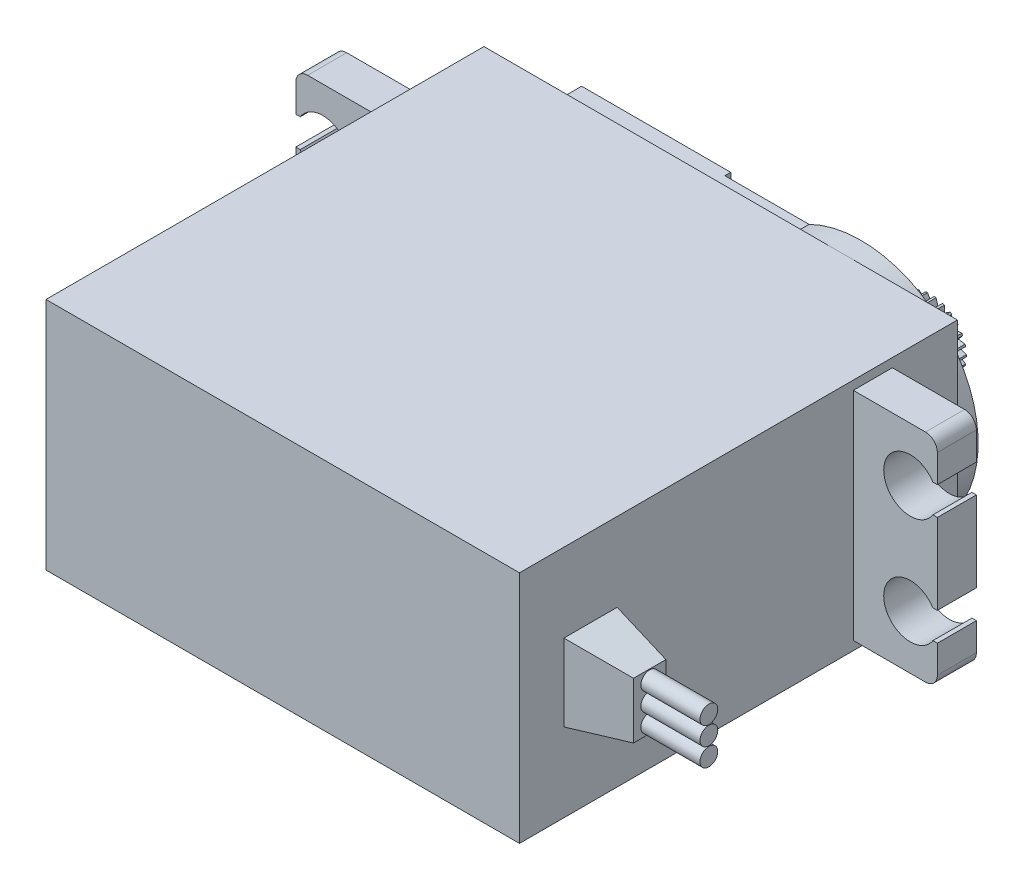
SolidWorks part; units mm, degrees
ref_plane "Front Plane" through (0, 0, 0) normal (0, 0, 1) x (1, 0, 0)
ref_plane "Top Plane" through (0, 0, 0) normal (0, 1, 0) x (1, 0, 0)
ref_plane "Right Plane" through (0, 0, 0) normal (1, 0, 0) x (0, 0, -1)
sketch "Sketch1" plane through (0, 0, 0) normal (0, 1, 0) x (1, 0, 0)
  line L1 (-20, -18.5) -> (20, -18.5)
  line L2 (-20, -18.5) -> (-20, 18.5)
  line L3 (-20, 18.5) -> (20, 18.5)
  line L4 (20, -18.5) -> (20, 18.5)
  line L5 (-20, -18.5) -> (20, 18.5) construction
  line L6 (-20, 18.5) -> (20, -18.5) construction
  point P0 (0, 0)
  dimension "D1" = 40
  dimension "D2" = 37
extrude "Boss-Extrude1" add sketch "Sketch1" along normal mid plane 19.8
sketch "Sketch2" plane through (0, 0, -18.5) normal (0, 0, -1) x (-1, 0, 0)
  line L0 (20.35, 0) -> (-20.35, 0) construction
  line L1 (-20, 9.9) -> (20, 9.9) construction
  line L2 (-20, 9.9) -> (-20, -9.9) construction
  line L3 (20, 9.9) -> (20, -9.9) construction
  line L4 (-5.7132, -8.875) -> (14, -8.875)
  line L6 (-5.7132, 8.875) -> (14, 8.875)
  line L7 (14, -8.875) -> (14, -4.625)
  line L8 (-5.7132, -8.875) -> (14, 8.875) construction
  line L9 (-5.7132, 8.875) -> (14, -8.875) construction
  line L10 (14, 4.625) -> (14, 8.875)
  circle A0 centre (-10.1, 0) radius 9.9
  arc A1 (14, 4.625) -> (14, -4.625) centre (10.3715, 0) cw
  point P8 (4.1434, 0)
  point P19 (16.25, 0)
  dimension "D4" = 3.75
  dimension "D1" = 17.75
  dimension "D2" = 6
  dimension "D3" = 9.25
extrude "Boss-Extrude2" add sketch "Sketch2" along normal blind 1.75 contours A0 | A0 L4 L7 L6
sketch "Sketch3" plane through (0, 0, -20.25) normal (0, 0, -1) x (-1, 0, 0)
  circle A0 centre (-10.1, 0) radius 6.55
  dimension "D1" = 13.1
extrude "Boss-Extrude3" add sketch "Sketch3" along normal blind 1.25
sketch "Sketch4" plane through (0, 0, -21.5) normal (0, 0, -1) x (-1, 0, 0)
  circle A0 centre (-10.1, 0) radius 5.375
  dimension "D1" = 10.75
extrude "Boss-Extrude4" add sketch "Sketch4" along normal blind 0.65
ref_plane "Plane1" through (10.1, 0, 0) normal (1, 0, 0) x (0, 0, -1)
sketch "Sketch5" plane through (-20, 0, 0) normal (-1, 0, 0) x (0, 0, 1)
  line L0 (20.35, 0) -> (-20.35, 0) construction
  line L1 (-13, -9.15) -> (-9.7, -9.15)
  line L2 (-13, -9.15) -> (-13, 9.15)
  line L3 (-13, 9.15) -> (-9.7, 9.15)
  line L4 (-9.7, -9.15) -> (-9.7, 9.15)
  line L5 (-13, -9.15) -> (-9.7, 9.15) construction
  line L6 (-13, 9.15) -> (-9.7, -9.15) construction
  line L7 (-18.5, 9.9) -> (-18.5, -9.9) construction
  point P0 (-11.35, 0)
  dimension "D1" = 18.3
  dimension "D2" = 3.3
  dimension "D3" = 5.5
extrude "Boss-Extrude5" add sketch "Sketch5" along normal blind 7.1
sketch "Sketch6" plane through (0, 0, -13) normal (0, 0, -1) x (-1, 0, 0)
  line L1 (20, 9.15) -> (20, -9.15) construction
  line L2 (27.1, 9.15) -> (20, 9.15) construction
  line L4 (27.1, 3.4) -> (27.1, 5.8)
  line L5 (27.1, 9.15) -> (27.1, -9.15) construction
  line L6 (27.1, 5.8) -> (26.7233, 5.8)
  line L7 (27.1, 3.4) -> (26.7233, 3.4)
  circle A0 centre (24.82, 4.6) radius 2.25
  point P11 (27.1, 4.6)
  line M5 (27.1, -9.15) -> (27.1, 9.15)
  dimension "D1" = 4.5
  dimension "D2" = 2.4
  dimension "D3" = 4.82
  dimension "D4" = 4.55
extrude "Cut-Extrude1" cut sketch "Sketch6" against normal up to surface (3.3 mm away) contours A0 L7 L6 M5 | A0 up to face at (-23.55, 0, -9.7)
mirror "Mirror1" about plane through (0, 0, 0) normal (0, 1, 0) of "Cut-Extrude1"
fillet "Fillet1" radius 1 2 edges at (-27.1, 9.15, -11.35) (-27.1, -9.15, -11.35)
mirror "Mirror4" about plane through (0, 0, 0) normal (1, 0, 0) of "Fillet1", "Boss-Extrude5", "Cut-Extrude1", "Mirror1"
sketch "Sketch8" plane through (0, 0, -20.25) normal (0, 0, -1) x (-1, 0, 0)
  line L0 (14, 4.625) -> (14, 8.875) construction
  line L1 (14, 8.875) -> (1.4, 8.875)
  line L2 (14, 8.875) -> (14, -8.875)
  line L3 (14, -8.875) -> (1.4, -8.875)
  line L4 (1.4, 8.875) -> (1.4, -8.875)
  line L5 (14, 4.625) -> (14, 8.875) construction
  line L6 (-5.7132, -8.875) -> (14, -8.875) construction
  line L7 (-5.7132, 8.875) -> (14, 8.875) construction
  arc A0 (1.4, 1.875) -> (1.4, -1.875) centre (1.4, 0) ccw
  line M3 (14, 8.875) -> (-5.7132, 8.875)
  line M5 (-5.7132, -8.875) -> (14, -8.875)
  line M6 (14, -8.875) -> (14, -4.625)
  line M8 (14, 4.625) -> (14, 8.875)
  dimension "D2" = 1.875
  dimension "D1" = 12.6
extrude "Boss-Extrude6" add sketch "Sketch8" along normal blind 0.5 contours L4 A0 | L4 L2 M3 M5 M6 M8
sketch "Sketch9" plane through (20, 0, 0) normal (1, 0, 0) x (0, 0, -1)
  line L0 (22.3575, 0) -> (-22.3575, 0) construction
  line L1 (-14.75, -3.25) -> (-10.25, -3.25)
  line L2 (-14.75, -3.25) -> (-14.75, 3.25)
  line L3 (-14.75, 3.25) -> (-10.25, 3.25)
  line L4 (-10.25, -3.25) -> (-10.25, 3.25)
  line L5 (-14.75, -3.25) -> (-10.25, 3.25) construction
  line L6 (-14.75, 3.25) -> (-10.25, -3.25) construction
  line L7 (-18.5, 9.9) -> (-18.5, -9.9) construction
  point P0 (-12.5, 0)
  dimension "D1" = 6.5
  dimension "D2" = 4.5
  dimension "D3" = 6
extrude "Boss-Extrude7" add sketch "Sketch9" along normal blind 5 draft 10
sketch "Sketch10" plane through (25, 0, 0) normal (1, 0, 0) x (0, 0, -1)
  line L0 (22.3575, 0) -> (-22.3575, 0) construction
  line L1 (-11.1316, 2.3684) -> (-13.8684, 2.3684) construction
  circle A0 centre (-12.5, 0) radius 0.75
  circle A1 centre (-12.5, 1.55) radius 0.75
  circle A2 centre (-12.5, -1.55) radius 0.75
  point P7 (-12.5, 2.3684)
  dimension "D1" = 1.5
  dimension "D2" = 1.5
  dimension "D3" = 1.5
  dimension "D4" = 1.55
  dimension "D5" = 1.55
extrude "Boss-Extrude9" add sketch "Sketch10" along normal blind 5
sketch "Sketch11" plane through (0, 0, -22.15) normal (0, 0, -1) x (-1, 0, 0)
  circle A0 centre (-10.1, 0) radius 3
  dimension "D1" = 6
extrude "Boss-Extrude10" add sketch "Sketch11" along normal blind 4
sketch "Sketch12" plane through (0, 0, -26.15) normal (0, 0, -1) x (-1, 0, 0)
  line L0 (-10.1, 3) -> (-10.1, 2.5)
  line L1 (-10.1, 2.5) -> (-9.8189, 2.9868)
  line L2 (-10.1, 2.5) -> (-10.3811, 2.9868)
  line L3 (-9.3821, 2.9128) -> (-9.5017, 2.4274)
  line L4 (-9.5017, 2.4274) -> (-9.1123, 2.8328)
  line L5 (-9.5017, 2.4274) -> (-9.6581, 2.9673)
  line L6 (-8.7058, 2.6564) -> (-8.9382, 2.2136)
  line L7 (-8.9382, 2.2136) -> (-8.4631, 2.5141)
  line L8 (-8.9382, 2.2136) -> (-8.9608, 2.7753)
  line L9 (-8.1106, 2.2455) -> (-8.4422, 1.8713)
  line L10 (-8.4422, 1.8713) -> (-7.909, 2.0493)
  line L11 (-8.4422, 1.8713) -> (-8.3298, 2.422)
  line L12 (-7.631, 1.7042) -> (-8.0425, 1.4202)
  line L13 (-8.0425, 1.4202) -> (-7.4822, 1.4654)
  line L14 (-8.0425, 1.4202) -> (-7.8016, 1.928)
  line L15 (-7.295, 1.0638) -> (-7.7625, 0.8865)
  line L16 (-7.7625, 0.8865) -> (-7.2076, 0.7963)
  line L17 (-7.7625, 0.8865) -> (-7.407, 1.3219)
  line L18 (-7.1219, 0.3616) -> (-7.6182, 0.3013)
  line L19 (-7.6182, 0.3013) -> (-7.1011, 0.081)
  line L20 (-7.6182, 0.3013) -> (-7.1688, 0.639)
  line L21 (-7.1219, -0.3616) -> (-7.6182, -0.3013)
  line L22 (-7.6182, -0.3013) -> (-7.1688, -0.639)
  line L23 (-7.6182, -0.3013) -> (-7.1011, -0.081)
  line L24 (-7.295, -1.0638) -> (-7.7625, -0.8865)
  line L25 (-7.7625, -0.8865) -> (-7.407, -1.3219)
  line L26 (-7.7625, -0.8865) -> (-7.2076, -0.7963)
  line L27 (-7.631, -1.7042) -> (-8.0425, -1.4202)
  line L28 (-8.0425, -1.4202) -> (-7.8016, -1.928)
  line L29 (-8.0425, -1.4202) -> (-7.4822, -1.4654)
  line L30 (-8.1106, -2.2455) -> (-8.4422, -1.8713)
  line L31 (-8.4422, -1.8713) -> (-8.3298, -2.422)
  line L32 (-8.4422, -1.8713) -> (-7.909, -2.0493)
  line L33 (-8.7058, -2.6564) -> (-8.9382, -2.2136)
  line L34 (-8.9382, -2.2136) -> (-8.9608, -2.7753)
  line L35 (-8.9382, -2.2136) -> (-8.4631, -2.5141)
  line L36 (-9.3821, -2.9128) -> (-9.5017, -2.4274)
  line L37 (-9.5017, -2.4274) -> (-9.6581, -2.9673)
  line L38 (-9.5017, -2.4274) -> (-9.1123, -2.8328)
  line L39 (-10.1, -3) -> (-10.1, -2.5)
  line L40 (-10.1, -2.5) -> (-10.3811, -2.9868)
  line L41 (-10.1, -2.5) -> (-9.8189, -2.9868)
  line L42 (-10.8179, -2.9128) -> (-10.6983, -2.4274)
  line L43 (-10.6983, -2.4274) -> (-11.0877, -2.8328)
  line L44 (-10.6983, -2.4274) -> (-10.5419, -2.9673)
  line L45 (-11.4942, -2.6564) -> (-11.2618, -2.2136)
  line L46 (-11.2618, -2.2136) -> (-11.7369, -2.5141)
  line L47 (-11.2618, -2.2136) -> (-11.2392, -2.7753)
  line L48 (-12.0894, -2.2455) -> (-11.7578, -1.8713)
  line L49 (-11.7578, -1.8713) -> (-12.291, -2.0493)
  line L50 (-11.7578, -1.8713) -> (-11.8702, -2.422)
  line L51 (-12.569, -1.7042) -> (-12.1575, -1.4202)
  line L52 (-12.1575, -1.4202) -> (-12.7178, -1.4654)
  line L53 (-12.1575, -1.4202) -> (-12.3984, -1.928)
  line L54 (-12.905, -1.0638) -> (-12.4375, -0.8865)
  line L55 (-12.4375, -0.8865) -> (-12.9924, -0.7963)
  line L56 (-12.4375, -0.8865) -> (-12.793, -1.3219)
  line L57 (-13.0781, -0.3616) -> (-12.5818, -0.3013)
  line L58 (-12.5818, -0.3013) -> (-13.0989, -0.081)
  line L59 (-12.5818, -0.3013) -> (-13.0312, -0.639)
  line L60 (-13.0781, 0.3616) -> (-12.5818, 0.3013)
  line L61 (-12.5818, 0.3013) -> (-13.0312, 0.639)
  line L62 (-12.5818, 0.3013) -> (-13.0989, 0.081)
  line L63 (-12.905, 1.0638) -> (-12.4375, 0.8865)
  line L64 (-12.4375, 0.8865) -> (-12.793, 1.3219)
  line L65 (-12.4375, 0.8865) -> (-12.9924, 0.7963)
  line L66 (-12.569, 1.7042) -> (-12.1575, 1.4202)
  line L67 (-12.1575, 1.4202) -> (-12.3984, 1.928)
  line L68 (-12.1575, 1.4202) -> (-12.7178, 1.4654)
  line L69 (-12.0894, 2.2455) -> (-11.7578, 1.8713)
  line L70 (-11.7578, 1.8713) -> (-11.8702, 2.422)
  line L71 (-11.7578, 1.8713) -> (-12.291, 2.0493)
  line L72 (-11.4942, 2.6564) -> (-11.2618, 2.2136)
  line L73 (-11.2618, 2.2136) -> (-11.2392, 2.7753)
  line L74 (-11.2618, 2.2136) -> (-11.7369, 2.5141)
  line L75 (-10.8179, 2.9128) -> (-10.6983, 2.4274)
  line L76 (-10.6983, 2.4274) -> (-10.5419, 2.9673)
  line L77 (-10.6983, 2.4274) -> (-11.0877, 2.8328)
  circle A0 centre (-10.1, 0) radius 3 construction
  arc A1 (-10.3811, 2.9868) -> (-9.8189, 2.9868) centre (-10.1, 0) cw
  arc A2 (-9.6581, 2.9673) -> (-9.1123, 2.8328) centre (-10.1, 0) cw
  arc A3 (-8.9608, 2.7753) -> (-8.4631, 2.5141) centre (-10.1, 0) cw
  arc A4 (-8.3298, 2.422) -> (-7.909, 2.0493) centre (-10.1, 0) cw
  arc A5 (-7.8016, 1.928) -> (-7.4822, 1.4654) centre (-10.1, 0) cw
  arc A6 (-7.407, 1.3219) -> (-7.2076, 0.7963) centre (-10.1, 0) cw
  arc A7 (-7.1688, 0.639) -> (-7.1011, 0.081) centre (-10.1, 0) cw
  arc A8 (-7.1011, -0.081) -> (-7.1688, -0.639) centre (-10.1, 0) cw
  arc A9 (-7.2076, -0.7963) -> (-7.407, -1.3219) centre (-10.1, 0) cw
  arc A10 (-7.4822, -1.4654) -> (-7.8016, -1.928) centre (-10.1, 0) cw
  arc A11 (-7.909, -2.0493) -> (-8.3298, -2.422) centre (-10.1, 0) cw
  arc A12 (-8.4631, -2.5141) -> (-8.9608, -2.7753) centre (-10.1, 0) cw
  arc A13 (-9.1123, -2.8328) -> (-9.6581, -2.9673) centre (-10.1, 0) cw
  arc A14 (-9.8189, -2.9868) -> (-10.3811, -2.9868) centre (-10.1, 0) cw
  arc A15 (-10.5419, -2.9673) -> (-11.0877, -2.8328) centre (-10.1, 0) cw
  arc A16 (-11.2392, -2.7753) -> (-11.7369, -2.5141) centre (-10.1, 0) cw
  arc A17 (-11.8702, -2.422) -> (-12.291, -2.0493) centre (-10.1, 0) cw
  arc A18 (-12.3984, -1.928) -> (-12.7178, -1.4654) centre (-10.1, 0) cw
  arc A19 (-12.793, -1.3219) -> (-12.9924, -0.7963) centre (-10.1, 0) cw
  arc A20 (-13.0312, -0.639) -> (-13.0989, -0.081) centre (-10.1, 0) cw
  arc A21 (-13.0989, 0.081) -> (-13.0312, 0.639) centre (-10.1, 0) cw
  arc A22 (-12.9924, 0.7963) -> (-12.793, 1.3219) centre (-10.1, 0) cw
  arc A23 (-12.7178, 1.4654) -> (-12.3984, 1.928) centre (-10.1, 0) cw
  arc A24 (-12.291, 2.0493) -> (-11.8702, 2.422) centre (-10.1, 0) cw
  arc A25 (-11.7369, 2.5141) -> (-11.2392, 2.7753) centre (-10.1, 0) cw
  arc A26 (-11.0877, 2.8328) -> (-10.5419, 2.9673) centre (-10.1, 0) cw
  point P110 (-10.1, 0)
  circle M4 centre (-10.1, 0) radius 3
  dimension "D1" = 0.5
  dimension "D2" = 30
  dimension "D3" = 30
  dimension "D4" = 26
extrude "Cut-Extrude3" cut sketch "Sketch12" against normal up to surface (4 mm away) contours L0 L1 M4 | L2 L0 M4 | L75 L76 M4 | L77 L75 M4 | L72 L73 M4 | L74 L72 M4 | L15 L16 M4 | L17 L15 M4 | L70 A24 L71 | L67 A23 L68 | L64 A22 L65 | L4 A2 L5 | L7 A3 L8 | L10 A4 L11 | L13 A5 L14 | L19 A7 L20 | L22 A8 L23 | L25 A9 L26 | L28 A10 L29 | L32 A11 L31 | L34 A12 L35 | L38 A13 L37 | L41 A14 L40 | L44 A15 L43 | L47 A16 L46 | L50 A17 L49 | L53 A18 L52 | L56 A19 L55 | L59 A20 L58 | L62 A21 L61 up to face at (7.1, 0, -22.15)
sketch "Sketch13" plane through (0, 0, -26.15) normal (0, 0, -1) x (-1, 0, 0)
  circle A0 centre (-10.1, 0) radius 1.3
  dimension "D1" = 2.6
extrude "Cut-Extrude4" cut sketch "Sketch13" against normal up to surface (4 mm away) up to face at (10.1, 0, -22.15)
sketch "Sketch14" plane through (0, 0, 0) normal (0, 1, 0) x (1, 0, 0)
  line L0 (20, 14.25) -> (27.1, 13)
  line L1 (20, -18.5) -> (20, 18.5) construction
  line L2 (20, 14.25) -> (20, 13)
  line L3 (20, 13) -> (27.1, 13)
  dimension "D1" = 4.25
extrude "Boss-Extrude11" add sketch "Sketch14" along normal mid plane 1
mirror "Mirror5" about plane through (0, 0, 0) normal (1, 0, 0) of "Boss-Extrude11"
